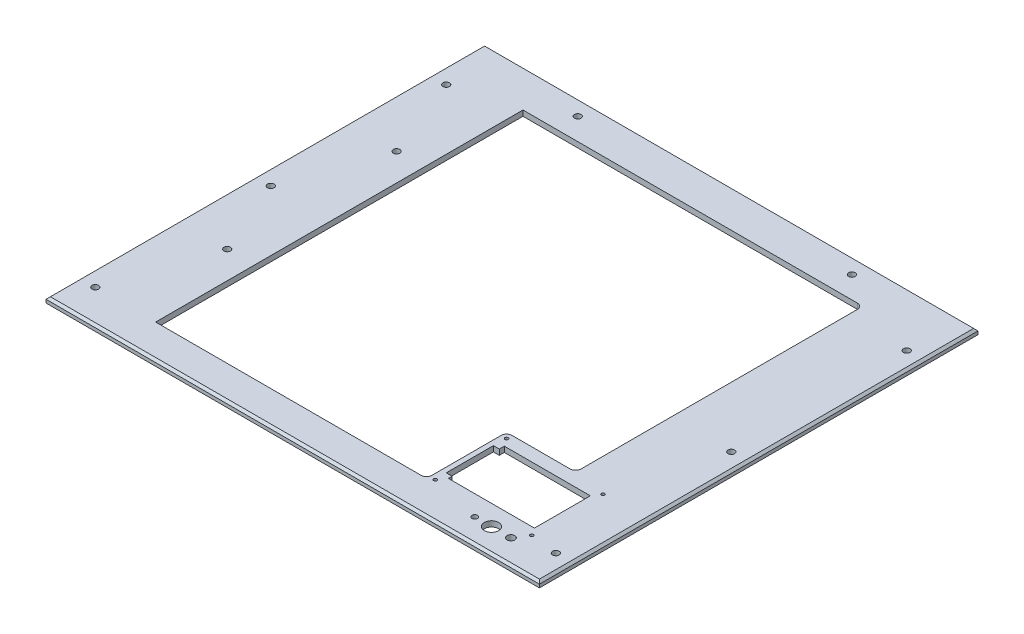
SolidWorks part; units mm, degrees
ref_plane "Alzado" through (0, 0, 0) normal (0, 0, 1) x (1, 0, 0)
ref_plane "Planta" through (0, 0, 0) normal (0, 1, 0) x (1, 0, 0)
ref_plane "Vista lateral" through (0, 0, 0) normal (1, 0, 0) x (0, 0, -1)
sketch "Croquis1" plane through (0, 0, 0) normal (0, 1, 0) x (1, 0, 0)
  line L0 (191.6732, -229.572) -> (261.6732, -229.572)
  line L1 (-188.3268, 170.428) -> (261.6732, 170.428)
  line L2 (-188.3268, 170.428) -> (-188.3268, -229.572)
  line L3 (-188.3268, -229.572) -> (-118.3268, -229.572)
  line L4 (261.6732, 170.428) -> (261.6732, -229.572)
  line L5 (138.6732, -186.172) -> (138.6732, -189.572)
  line L6 (-118.3268, -199.572) -> (-118.3268, 135.428)
  line L7 (-118.3268, 135.428) -> (191.6732, 135.428)
  line L8 (191.6732, -126.572) -> (191.6732, 135.428)
  line L9 (-118.3268, -229.572) -> (191.6732, -229.572)
  line L10 (138.6732, -138.572) -> (217.1232, -138.572)
  line L11 (-118.3268, -199.572) -> (128.7232, -199.572)
  line L12 (138.6732, -138.572) -> (138.6732, -143.172)
  line L13 (138.6732, -189.572) -> (217.1232, -189.572)
  line L14 (217.1232, -138.572) -> (217.1232, -189.572)
  line L15 (138.6732, -143.172) -> (133.2732, -143.172)
  line L17 (138.6732, -186.172) -> (133.2732, -186.172)
  line L18 (133.2732, -143.172) -> (133.2732, -186.172)
  line L19 (191.6732, -126.572) -> (128.7232, -126.572)
  line L22 (128.7232, -126.572) -> (128.7232, -199.572)
  circle A0 centre (-173.3268, 120.428) radius 3
  circle A1 centre (-173.3268, -199.572) radius 3
  circle A2 centre (246.6732, -199.572) radius 3
  circle A3 centre (246.6732, 120.428) radius 3
  circle A4 centre (-173.3268, -39.572) radius 3
  circle A5 centre (246.6732, -39.572) radius 3
  circle A6 centre (-88.3268, 155.428) radius 3
  circle A7 centre (161.6732, 155.428) radius 3
  circle A8 centre (133.7232, -131.572) radius 1.5
  circle A9 centre (133.7232, -196.572) radius 1.5
  circle A10 centre (221.6732, -196.572) radius 1.5
  circle A11 centre (221.6732, -131.572) radius 1.5
  circle A12 centre (196.3232, -207.922) radius 6.5
  circle A13 centre (214.0732, -207.922) radius 3.5
  circle A14 centre (181.0732, -207.922) radius 2.5
  circle A15 centre (-143.3268, 45.178) radius 3
  circle A16 centre (-143.3268, -109.322) radius 3
  dimension "D3" = 6
  dimension "D4" = 6
  dimension "D5" = 6
  dimension "D6" = 6
  dimension "D7" = 6
  dimension "D8" = 6
  dimension "D14" = 6
  dimension "D15" = 6
  dimension "D22" = 3
  dimension "D23" = 3
  dimension "D24" = 3
  dimension "D25" = 3
  dimension "D35" = 7
  dimension "D36" = 13
  dimension "D37" = 5
  dimension "D48" = 6
  dimension "D49" = 6
  dimension "D1" = 450
  dimension "D2" = 400
  dimension "D9" = 50
  dimension "D10" = 30
  dimension "D11" = 160
  dimension "D12" = 15
  dimension "D13" = 15
  dimension "D16" = 100
  dimension "D17" = 100
  dimension "D18" = 15
  dimension "D19" = 35
  dimension "D20" = 70
  dimension "D21" = 70
  dimension "D26" = 4.95
  dimension "D27" = 7
  dimension "D28" = 7
  dimension "D29" = 87.95
  dimension "D30" = 4.55
  dimension "D31" = 65
  dimension "D32" = 4.6
  dimension "D33" = 3.4
  dimension "D34" = 5.4
  dimension "D38" = 7.6
  dimension "D39" = 17.75
  dimension "D40" = 15.25
  dimension "D41" = 11.35
  dimension "D42" = 40
  dimension "D43" = 5
  dimension "D44" = 5
  dimension "D45" = 70
  dimension "D46" = 10
  dimension "D47" = 30
  dimension "D50" = 25
  dimension "D51" = 154.5
  dimension "D52" = 90.25
extrude "Saliente-Extruir1" add sketch "Croquis1" along normal blind 5
chamfer "Chaflán1" distance 2 angle 45 4 edges at (261.6732, 5, 29.572) (36.6732, 5, -170.428) (-188.3268, 5, 29.572) (36.6732, 5, 229.572)
fillet "Redondeo1" radius 5 4 edges at (128.7232, 2.5, 199.572) (191.6732, 2.5, -135.428) (191.6732, 2.5, 126.572) (128.7232, 2.5, 126.572)
